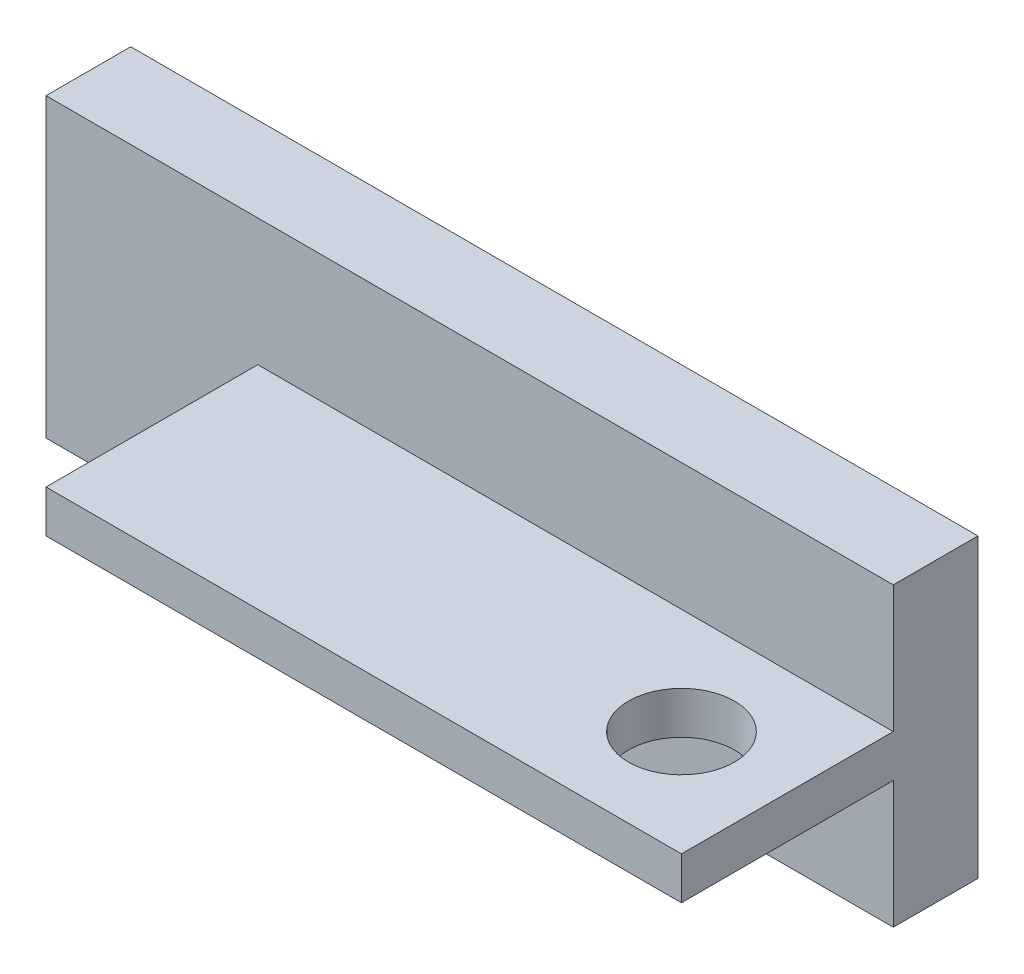
SolidWorks part; units mm, degrees
ref_plane "Front Plane" through (0, 0, 0) normal (0, 0, 1) x (1, 0, 0)
ref_plane "Top Plane" through (0, 0, 0) normal (0, 1, 0) x (1, 0, 0)
ref_plane "Right Plane" through (0, 0, 0) normal (1, 0, 0) x (0, 0, -1)
sketch "Sketch1" plane through (0, 0, 0) normal (0, 1, 0) x (1, 0, 0)
  line L1 (0, 0) -> (-200, 0)
  line L2 (0, 0) -> (0, 70)
  line L3 (0, 70) -> (-200, 70)
  line L4 (-200, 0) -> (-200, 70)
  dimension "D1" = 200
  dimension "D2" = 70
extrude "Boss-Extrude1" add sketch "Sketch1" along normal blind 10
sketch "Sketch2" plane through (0, 10, 0) normal (0, 1, 0) x (1, 0, 0)
  line L0 (-200, 70) -> (-200, 0) construction
  line L1 (0, 70) -> (-200, 70)
  line L2 (0, 70) -> (0, 50)
  line L3 (0, 50) -> (-200, 50)
  line L4 (-200, 70) -> (-200, 50)
  dimension "D1" = 20
extrude "Boss-Extrude2" add sketch "Sketch2" along normal blind 30
sketch "Sketch3" plane through (0, 0, 0) normal (0, -1, 0) x (1, 0, 0)
  line L0 (-200, -70) -> (-200, 0) construction
  line L1 (0, -70) -> (-200, -70)
  line L2 (0, -70) -> (0, -50)
  line L3 (0, -50) -> (-200, -50)
  line L4 (-200, -70) -> (-200, -50)
  dimension "D1" = 20
extrude "Boss-Extrude3" add sketch "Sketch3" along normal blind 30
sketch "Sketch4" plane through (0, 10, 0) normal (0, 1, 0) x (1, 0, 0)
  line L0 (-200, 50) -> (-200, 0) construction
  line L2 (-200, 0) -> (0, 0) construction
  line L3 (0, 0) -> (0, 50) construction
  circle A0 centre (-25, 25) radius 12.5
  circle A1 centre (-175, 25) radius 12.5
  point P8 (-182.2861, 0)
  point P9 (-175.8208, 28.9755)
  dimension "D1" = 25
  dimension "D2" = 25
  dimension "D3" = 25
  dimension "D4" = 25
extrude "Cut-Extrude1" cut sketch "Sketch4" against normal blind 30
sketch "Sketch5" plane through (0, 10, 0) normal (0, 1, 0) x (1, 0, 0)
  line L0 (-200, 50) -> (0, 50) construction
  line L1 (-200, 0) -> (-150, 0)
  line L2 (-200, 0) -> (-200, 50)
  line L3 (-200, 50) -> (-150, 50)
  line L4 (-150, 0) -> (-150, 50)
  dimension "D1" = 50
extrude "Cut-Extrude2" cut sketch "Sketch5" against normal blind 30
equation "\"D4@Sketch4\"=\"D2@Sketch4\""
